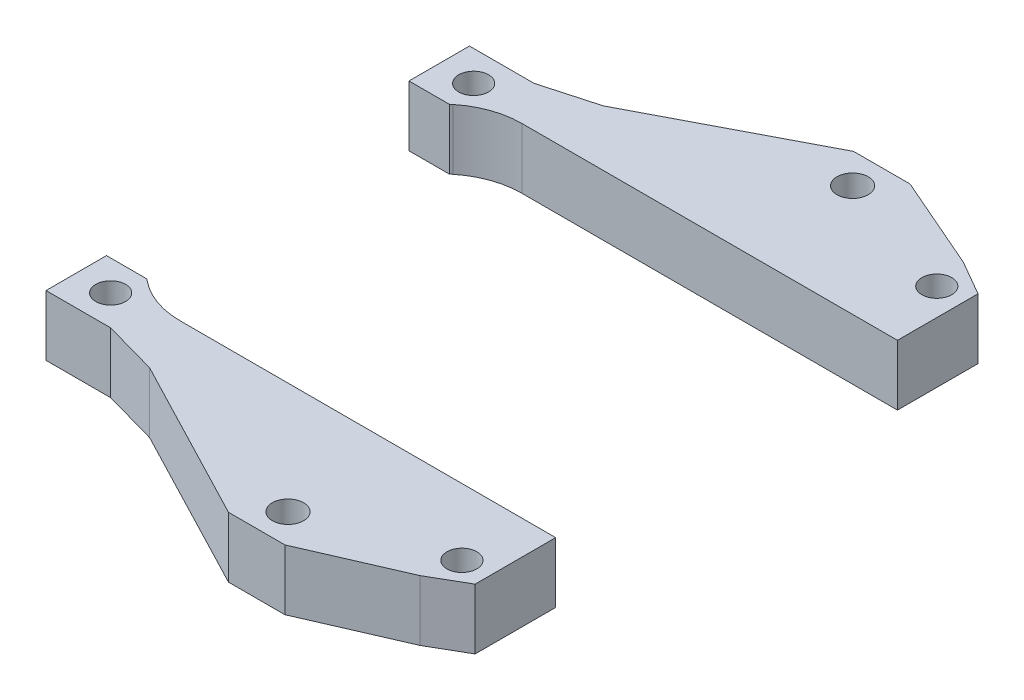
SolidWorks part; units mm, degrees
ref_plane "前视基准面" through (0, 0, 0) normal (0, 0, 1) x (1, 0, 0)
ref_plane "上视基准面" through (0, 0, 0) normal (0, 1, 0) x (1, 0, 0)
ref_plane "右视基准面" through (0, 0, 0) normal (1, 0, 0) x (0, 0, -1)
sketch "草图1" plane through (0, 0, 0) normal (0, 1, 0) x (1, 0, 0)
  line L1 (-40, 31) -> (40, 31)
  line L2 (-40, 31) -> (-40, -31)
  line L3 (-40, -31) -> (40, -31)
  line L4 (40, 31) -> (40, -31)
  line L5 (-40, 31) -> (40, -31) construction
  line L6 (-40, -31) -> (40, 31) construction
  point P0 (0, 0)
  dimension "D1" = 62
  dimension "D2" = 80
extrude "凸台-拉伸1" add sketch "草图1" along normal blind 6
sketch "草图2" plane through (0, 0, 0) normal (0, -1, 0) x (1, 0, 0)
  line L0 (40, 24.9378) -> (26.75, 32.5877) construction
  line L1 (22.75, 32.5877) -> (5.2776, 22.5) construction
  line L2 (40, 24.9378) -> (26.75, 32.5877)
  line L3 (22.75, 32.5877) -> (5.2776, 22.5)
  line L4 (-24.5, 21) -> (-0.0847, 21)
  line L5 (-0.0847, 21) -> (5.2776, 22.5)
  line L6 (-24.5, 21) -> (-24.5, 15)
  line L7 (-71.5, 15) -> (-2.5, 15) construction
  line L8 (-24.5, 15) -> (-2.5, 15)
  line L9 (-2.5, 15) -> (-0.0847, 16.95)
  line L10 (-0.0847, 16.95) -> (12.2153, 16.95)
  line L11 (12.2153, 16.95) -> (40, 16.95)
  line L12 (40, 31) -> (40, -31) construction
  line L13 (40, 16.95) -> (40, 24.9378)
  line L14 (0, 0) -> (40, 0) construction
  line L15 (40, -16.95) -> (40, -24.9378)
  line L16 (12.2153, -16.95) -> (40, -16.95)
  line L17 (-0.0847, -16.95) -> (12.2153, -16.95)
  line L18 (-2.5, -15) -> (-0.0847, -16.95)
  line L19 (-24.5, -15) -> (-2.5, -15)
  line L20 (-24.5, -21) -> (-24.5, -15)
  line L21 (-0.0847, -21) -> (5.2776, -22.5)
  line L22 (-24.5, -21) -> (-0.0847, -21)
  line L23 (22.75, -32.5877) -> (5.2776, -22.5)
  line L24 (40, -24.9378) -> (26.75, -32.5877)
  arc A0 (26.75, 32.5877) -> (22.75, 32.5877) centre (24.75, 29.1236) ccw construction
  arc A1 (26.75, 32.5877) -> (22.75, 32.5877) centre (24.75, 29.1236) ccw
  arc A2 (26.75, -32.5877) -> (22.75, -32.5877) centre (24.75, -29.1236) cw
extrude "切除-拉伸1" cut sketch "草图2" against normal blind 20
sketch "草图4" plane through (0, 6, 0) normal (0, 1, 0) x (1, 0, 0)
  line L1 (29.5, 31) -> (20, 31) construction
  line L2 (40, 16.95) -> (40, 24.9378) construction
  circle A0 centre (24.5, 28) radius 1.55
  dimension "D1" = 3
  dimension "D2" = 15.5
extrude "切除-拉伸2" cut sketch "草图4" against normal blind 20
sketch "草图5" plane through (0, 6, 0) normal (0, 1, 0) x (1, 0, 0)
  line L0 (20, -31) -> (29.5, -31) construction
  line L1 (40, -24.9378) -> (40, -16.95) construction
  circle A0 centre (24.5, -28) radius 1.55
  dimension "D1" = 3
  dimension "D2" = 15.5
extrude "切除-拉伸3" cut sketch "草图5" against normal blind 20
sketch "草图6" plane through (0, 0, 0) normal (0, -1, 0) x (1, 0, 0)
  line L0 (-0.0847, -16.95) -> (40, -16.95) construction
  line L1 (40, -24.9378) -> (40, 24.9378) construction
  line L2 (-24.5, -15) -> (-2.5, -15) construction
  line L3 (-0.0847, 21) -> (-0.0847, -21) construction
  line L4 (-24.5, -21) -> (-0.0847, -21) construction
  line L5 (-24.5, -15) -> (-6.5, -15)
  line L6 (-24.5, -15) -> (-24.5, -21)
  line L7 (-24.5, -21) -> (-6.5, -21)
  line L8 (-6.5, -15) -> (-6.5, -21)
  circle A0 centre (37.3, -23.55) radius 1.48
  circle A1 centre (-3.0847, -18) radius 1.48
  dimension "D1" = 6.6
  dimension "D3" = 2.96
  dimension "D4" = 3
  dimension "D2" = 2.7
  dimension "D5" = 3
  dimension "D6" = 18
extrude "切除-拉伸4" cut sketch "草图6" against normal blind 20
sketch "草图7" plane through (0, 0, 0) normal (0, -1, 0) x (1, 0, 0)
  line L0 (-24.5, 15) -> (-2.5, 15) construction
  line L1 (-24.5, 21) -> (-6.5, 21)
  line L2 (-24.5, 21) -> (-24.5, 15)
  line L3 (-24.5, 15) -> (-6.5, 15)
  line L4 (-6.5, 21) -> (-6.5, 15)
  line L5 (-0.0847, 16.95) -> (-0.0847, 21) construction
  line L6 (40, 24.9378) -> (40, 16.95) construction
  line L7 (-0.0847, 16.95) -> (40, 16.95) construction
  circle A0 centre (37.3, 23.55) radius 1.48
  circle A1 centre (-3.0847, 18) radius 1.48
  dimension "D1" = 18
  dimension "D2" = 3
  dimension "D3" = 3
  dimension "D4" = 2.7
  dimension "D5" = 6.6
extrude "切除-拉伸5" cut sketch "草图7" against normal blind 20
sketch "草图8" plane through (0, 6, 0) normal (0, 1, 0) x (1, 0, 0)
  line L0 (5.2776, 22.5) -> (21.6, 31)
  line L2 (27.2, 31) -> (36.5359, 26.9378)
  line L10 (-6.5, 21) -> (-6.5, 15)
  line L11 (-6.5, 15) -> (-2.5, 15)
  line L12 (-2.5, 15) -> (-0.0847, 16.95)
  line L13 (-0.0847, 16.95) -> (40, 16.95)
  line L14 (40, 16.95) -> (40, 24.9378)
  line L15 (40, 24.9378) -> (29.5, 31)
  line L16 (29.5, 31) -> (20, 31)
  line L17 (20, 31) -> (5.2776, 22.5)
  line L18 (5.2776, 22.5) -> (-0.0847, 21)
  line L19 (-0.0847, 21) -> (-6.5, 21)
  line L20 (-6.5, 21) -> (-6.5, 15)
  line L21 (-6.5, 15) -> (-2.5, 15)
  line L22 (-2.5, 15) -> (-0.0847, 16.95)
  line L23 (-0.0847, 16.95) -> (40, 16.95)
  line L24 (40, 16.95) -> (40, 24.9378)
  line L25 (40, 24.9378) -> (29.5, 31)
  line L26 (29.5, 31) -> (20, 31)
  line L27 (20, 31) -> (5.2776, 22.5)
  line L28 (5.2776, 22.5) -> (-0.0847, 21)
  line L29 (-0.0847, 21) -> (-6.5, 21)
  dimension "D2" = 1.6
  dimension "D3" = 2.3
  dimension "D4" = 2
  dimension "D1" = 0
extrude "切除-拉伸6" cut sketch "草图8" against normal blind 20
sketch "草图9" plane through (0, 6, 0) normal (0, 1, 0) x (1, 0, 0)
  line L0 (5.2776, -22.5) -> (21.6, -31)
  line L1 (27.2, -31) -> (36.5359, -26.9378)
  line L10 (-6.5, -15) -> (-6.5, -21)
  line L11 (-6.5, -21) -> (-0.0847, -21)
  line L12 (-0.0847, -21) -> (5.2776, -22.5)
  line L13 (5.2776, -22.5) -> (20, -31)
  line L14 (20, -31) -> (29.5, -31)
  line L15 (29.5, -31) -> (40, -24.9378)
  line L16 (40, -24.9378) -> (40, -16.95)
  line L17 (40, -16.95) -> (-0.0847, -16.95)
  line L18 (-0.0847, -16.95) -> (-2.5, -15)
  line L19 (-2.5, -15) -> (-6.5, -15)
  line L20 (-6.5, -15) -> (-6.5, -21)
  line L21 (-6.5, -21) -> (-0.0847, -21)
  line L22 (-0.0847, -21) -> (5.2776, -22.5)
  line L23 (5.2776, -22.5) -> (20, -31)
  line L24 (20, -31) -> (29.5, -31)
  line L25 (29.5, -31) -> (40, -24.9378)
  line L26 (40, -24.9378) -> (40, -16.95)
  line L27 (40, -16.95) -> (-0.0847, -16.95)
  line L28 (-0.0847, -16.95) -> (-2.5, -15)
  line L29 (-2.5, -15) -> (-6.5, -15)
  line M16 (5.2776, -22.5) -> (20, -31)
  line M17 (20, -31) -> (29.5, -31)
  line M18 (29.5, -31) -> (40, -24.9378)
  dimension "D2" = 1.6
  dimension "D3" = 2.3
  dimension "D4" = 2
  dimension "D1" = 0
extrude "切除-拉伸7" cut sketch "草图9" against normal blind 20 contours L0 M16 M17 | L1 M17 M18
fillet "圆角3" radius 8 1 edges at (-0.0847, 3, -16.95)
fillet "圆角4" radius 8 1 edges at (-0.0847, 3, 16.95)
